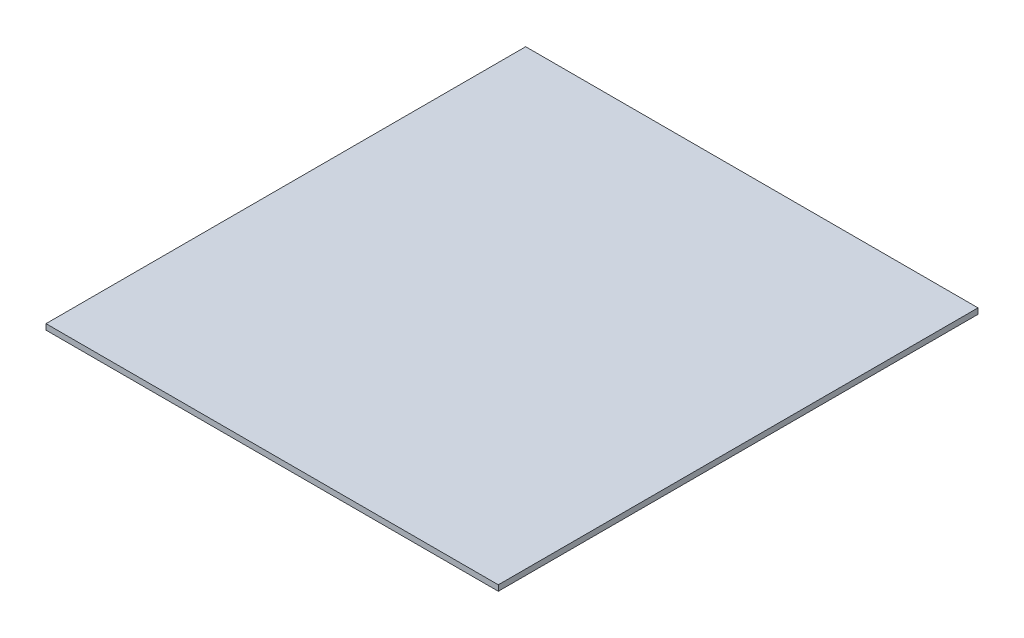
SolidWorks part; units mm, degrees
material "1060 Alloy"
ref_plane "Front Plane" through (0, 0, 0) normal (0, 0, 1) x (1, 0, 0)
ref_plane "Top Plane" through (0, 0, 0) normal (0, 1, 0) x (1, 0, 0)
ref_plane "Right Plane" through (0, 0, 0) normal (1, 0, 0) x (0, 0, -1)
other "Center of Mass"
sketch "Sketch1" plane through (0, 0, 0) normal (0, 1, 0) x (1, 0, 0)
  line L5 (-78.5, -83.25) -> (78.5, -83.25)
  line L6 (-78.5, -83.25) -> (-78.5, 83.25)
  line L7 (-78.5, 83.25) -> (78.5, 83.25)
  line L8 (78.5, -83.25) -> (78.5, 83.25)
  line L9 (-78.5, -83.25) -> (78.5, 83.25) construction
  line L10 (-78.5, 83.25) -> (78.5, -83.25) construction
  point P0 (0, 0)
  dimension "D1" = 157
  dimension "D2" = 166.5
extrude "Boss-Extrude1" add sketch "Sketch1" along normal blind 1.96
